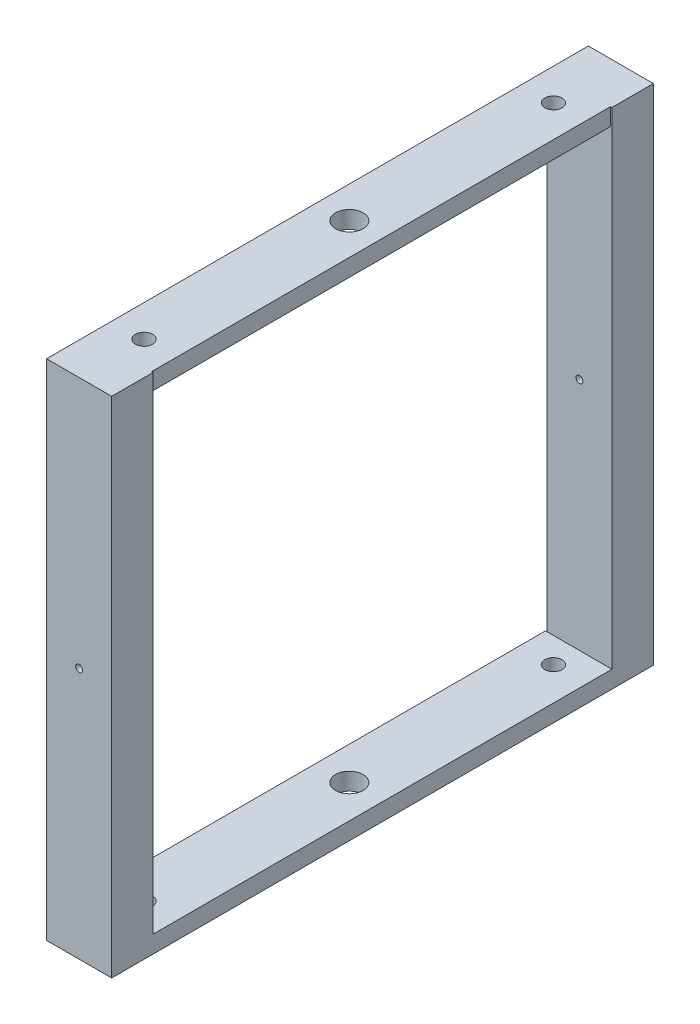
SolidWorks part; units mm, degrees
ref_plane "Front Plane" through (0, 0, 0) normal (0, 0, 1) x (1, 0, 0)
ref_plane "Top Plane" through (0, 0, 0) normal (0, 1, 0) x (1, 0, 0)
ref_plane "Right Plane" through (0, 0, 0) normal (1, 0, 0) x (0, 0, -1)
sketch "Sketch1" plane through (0, 0, 0) normal (0, 1, 0) x (1, 0, 0)
  line L1 (-66.5, -66.5) -> (66.5, -66.5)
  line L2 (-66.5, -66.5) -> (-66.5, 66.5)
  line L3 (-66.5, 66.5) -> (66.5, 66.5)
  line L4 (66.5, -66.5) -> (66.5, 66.5)
  line L5 (-66.5, -66.5) -> (66.5, 66.5) construction
  line L6 (-66.5, 66.5) -> (66.5, -66.5) construction
  point P0 (0, 0)
extrude "Boss-Extrude2" add sketch "Sketch1" along normal blind 136
sketch "Sketch2" plane through (0, 0, 66.5) normal (0, 0, 1) x (1, 0, 0)
  line L0 (66.5, 136) -> (66.5, 0) construction
  line L1 (-66.5, 136) -> (66.5, 136)
  line L2 (-66.5, 136) -> (-66.5, 127)
  line L3 (-66.5, 127) -> (66.5, 127)
  line L4 (66.5, 136) -> (66.5, 127)
  line L6 (-66.5, 0) -> (66.5, 0)
  line L7 (-66.5, 0) -> (-66.5, 9)
  line L8 (-66.5, 9) -> (66.5, 9)
  line L9 (66.5, 0) -> (66.5, 9)
  line L10 (-66.5, 127) -> (66.5, 127)
  line L11 (-66.5, 127) -> (-66.5, 9)
  line L12 (-66.5, 9) -> (66.5, 9)
  line L13 (66.5, 127) -> (66.5, 9)
  line M2 (66.5, 0) -> (66.5, 136)
  line M4 (-66.5, 136) -> (-66.5, 0)
extrude "Cut-Extrude1" cut sketch "Sketch2" against normal blind 136 contours L8 L3 M4 M2
sketch "Sketch4" plane through (0, 9, 0) normal (0, 1, 0) x (1, 0, 0)
  line L0 (0, 66.5) -> (0, -66.5) construction
  line L1 (-66.5, 66.5) -> (66.5, 66.5) construction
  line L2 (-66.5, -66.5) -> (66.5, -66.5) construction
  line L3 (0, -66.5) -> (33.25, -66.5) construction
  line L4 (33.25, -66.5) -> (33.25, 66.5) construction
  line L5 (0, 0) -> (66.5, 0) construction
  line L6 (66.5, 66.5) -> (66.5, -66.5) construction
  line L7 (66.5, 0) -> (66.5, 33.25) construction
  line L8 (66.5, 33.25) -> (0, 33.25) construction
  line L9 (0, 33.25) -> (0, -33.25) construction
  line L10 (0, -33.25) -> (66.5, -33.25) construction
  line L11 (43.75, 43.75) -> (22.75, 43.75)
  line L12 (43.75, -22.75) -> (22.75, -22.75)
  line L13 (43.75, -22.75) -> (43.75, -43.75)
  line L14 (43.75, -43.75) -> (22.75, -43.75)
  line L15 (22.75, -22.75) -> (22.75, -43.75)
  line L16 (43.75, -22.75) -> (22.75, -43.75) construction
  line L17 (43.75, -43.75) -> (22.75, -22.75) construction
  line L18 (46.25, -20.25) -> (20.25, -20.25)
  line L19 (46.25, -20.25) -> (46.25, -46.25)
  line L20 (46.25, -46.25) -> (20.25, -46.25)
  line L21 (20.25, -20.25) -> (20.25, -46.25)
  line L22 (46.25, -20.25) -> (20.25, -46.25) construction
  line L23 (46.25, -46.25) -> (20.25, -20.25) construction
  line L24 (22.75, 22.75) -> (22.75, 43.75)
  line L25 (43.75, 22.75) -> (22.75, 22.75)
  line L26 (43.75, 22.75) -> (43.75, 43.75)
  line L27 (46.25, 46.25) -> (20.25, 46.25)
  line L28 (20.25, 20.25) -> (20.25, 46.25)
  line L29 (46.25, 20.25) -> (20.25, 20.25)
  line L30 (46.25, 20.25) -> (46.25, 46.25)
  line L31 (46.25, 46.25) -> (20.25, 20.25) construction
  line L32 (46.25, 20.25) -> (20.25, 46.25) construction
  line L34 (43.75, -43.75) -> (46.25, -43.75)
  line L35 (43.75, -43.75) -> (43.75, -22.75)
  line L36 (43.75, -22.75) -> (46.25, -22.75)
  line L37 (46.25, -43.75) -> (46.25, -22.75)
  line L38 (43.75, 22.75) -> (46.25, 22.75)
  line L39 (43.75, 22.75) -> (43.75, 43.75)
  line L40 (43.75, 43.75) -> (46.25, 43.75)
  line L41 (46.25, 22.75) -> (46.25, 43.75)
  point P18 (33.25, -33.25)
  point P23 (33.25, -33.25)
  point P36 (33.25, 33.25)
extrude "Boss-Extrude3" add sketch "Sketch4" along normal blind 10.5 contours L12 L36 L19 L18 L21 L20 L34 L14 L15 | L11 L40 L30 L27 L28 L29 L38 L25 L24
sketch "Sketch5" plane through (22.75, 0, 0) normal (1, 0, 0) x (0, 0, -1)
  line L0 (-22.75, 19.5) -> (-22.75, 9) construction
  line L1 (-43.75, 19.5) -> (-22.75, 19.5)
  line L2 (-43.75, 19.5) -> (-43.75, 16.5)
  line L3 (-43.75, 16.5) -> (-22.75, 16.5)
  line L4 (-22.75, 19.5) -> (-22.75, 16.5)
  line L5 (43.75, 19.5) -> (43.75, 9) construction
  line L6 (22.75, 19.5) -> (43.75, 19.5)
  line L7 (22.75, 19.5) -> (22.75, 16.5)
  line L8 (22.75, 16.5) -> (43.75, 16.5)
  line L9 (43.75, 19.5) -> (43.75, 16.5)
extrude "Boss-Extrude4" add sketch "Sketch5" along normal up to surface (23.5 mm away) up to face at (46.25, 14.25, 45)
sketch "Sketch6" plane through (0, 19.5, 0) normal (0, 1, 0) x (1, 0, 0)
  line L0 (46.25, -46.25) -> (46.25, -20.25) construction
  line L1 (46.25, 20.25) -> (46.25, 46.25) construction
  line L2 (67.25, -41.85) -> (25.25, -41.85)
  line L3 (67.25, -41.85) -> (67.25, -24.65)
  line L4 (67.25, -24.65) -> (25.25, -24.65)
  line L5 (25.25, -41.85) -> (25.25, -24.65)
  line L6 (67.25, -41.85) -> (25.25, -24.65) construction
  line L7 (67.25, -24.65) -> (25.25, -41.85) construction
  line L9 (67.25, 24.65) -> (25.25, 24.65)
  line L10 (67.25, 24.65) -> (67.25, 41.85)
  line L11 (67.25, 41.85) -> (25.25, 41.85)
  line L12 (25.25, 24.65) -> (25.25, 41.85)
  line L13 (67.25, 24.65) -> (25.25, 41.85) construction
  line L14 (67.25, 41.85) -> (25.25, 24.65) construction
  point P4 (46.25, -33.25)
  point P13 (46.25, 33.25)
extrude "Cut-Extrude2" cut sketch "Sketch6" against normal up to surface (3 mm away) up to face at (34.5, 16.5, -33.25)
sketch "Sketch7" plane through (0, 127, 0) normal (0, -1, 0) x (1, 0, 0)
  line L0 (0, 66.5) -> (0, -66.5) construction
  line L1 (-66.5, 66.5) -> (66.5, 66.5) construction
  line L2 (-66.5, -66.5) -> (66.5, -66.5) construction
  line L3 (0, -66.5) -> (-33.25, -66.5) construction
  line L4 (-33.25, -66.5) -> (-33.25, 66.5) construction
  line L5 (-33.25, 66.5) -> (-66.5, 66.5) construction
  line L6 (-66.5, 66.5) -> (-66.5, 0) construction
  line L8 (-66.5, 0) -> (0, 0) construction
  line L9 (0, 0) -> (0, -33.25) construction
  line L10 (0, -33.25) -> (-66.5, -33.25) construction
  line L11 (-66.5, -66.5) -> (-66.5, 66.5) construction
  line L12 (-66.5, -33.25) -> (-66.5, 33.25) construction
  line L13 (-66.5, 33.25) -> (0, 33.25) construction
  line L14 (-22.75, -22.75) -> (-43.75, -22.75)
  line L15 (-22.75, 43.75) -> (-43.75, 43.75)
  line L16 (-22.75, 43.75) -> (-22.75, 22.75)
  line L17 (-22.75, 22.75) -> (-43.75, 22.75)
  line L18 (-43.75, 43.75) -> (-43.75, 22.75)
  line L19 (-22.75, 43.75) -> (-43.75, 22.75) construction
  line L20 (-22.75, 22.75) -> (-43.75, 43.75) construction
  line L21 (-20.25, 46.25) -> (-46.25, 46.25)
  line L22 (-20.25, 46.25) -> (-20.25, 20.25)
  line L23 (-20.25, 20.25) -> (-46.25, 20.25)
  line L24 (-46.25, 46.25) -> (-46.25, 20.25)
  line L25 (-20.25, 46.25) -> (-46.25, 20.25) construction
  line L26 (-20.25, 20.25) -> (-46.25, 46.25) construction
  line L27 (-43.75, -43.75) -> (-43.75, -22.75)
  line L28 (-22.75, -43.75) -> (-43.75, -43.75)
  line L29 (-22.75, -43.75) -> (-22.75, -22.75)
  line L30 (-20.25, -20.25) -> (-46.25, -20.25)
  line L31 (-46.25, -46.25) -> (-46.25, -20.25)
  line L32 (-20.25, -46.25) -> (-46.25, -46.25)
  line L33 (-20.25, -46.25) -> (-20.25, -20.25)
  line L34 (-20.25, -20.25) -> (-46.25, -46.25) construction
  line L35 (-20.25, -46.25) -> (-46.25, -20.25) construction
  line L36 (-43.75, -22.75) -> (-46.25, -22.75)
  line L37 (-43.75, 43.75) -> (-46.25, 43.75)
  line L38 (-43.75, 43.75) -> (-43.75, 22.75)
  line L39 (-43.75, 22.75) -> (-46.25, 22.75)
  line L40 (-46.25, 43.75) -> (-46.25, 22.75)
  line L41 (-46.25, -43.75) -> (-46.25, -22.75)
  line L42 (-43.75, -43.75) -> (-46.25, -43.75)
  line L43 (-43.75, -43.75) -> (-43.75, -22.75)
  point P17 (-33.25, 33.25)
  point P24 (-33.25, 33.25)
  point P37 (-33.25, -33.25)
extrude "Boss-Extrude5" add sketch "Sketch7" along normal blind 10.5 contours L17 L39 L24 L23 L22 L21 L37 L15 L16 | L28 L42 L31 L32 L33 L30 L36 L14 L29
sketch "Sketch8" plane through (-22.75, 0, 0) normal (-1, 0, 0) x (0, 0, 1)
  line L0 (22.75, 116.5) -> (22.75, 127) construction
  line L1 (43.75, 116.5) -> (22.75, 116.5)
  line L2 (43.75, 116.5) -> (43.75, 119.5)
  line L3 (43.75, 119.5) -> (22.75, 119.5)
  line L4 (22.75, 116.5) -> (22.75, 119.5)
  line L5 (-22.75, 116.5) -> (-22.75, 127) construction
  line L6 (-43.75, 116.5) -> (-22.75, 116.5)
  line L7 (-43.75, 116.5) -> (-43.75, 119.5)
  line L8 (-43.75, 119.5) -> (-22.75, 119.5)
  line L9 (-22.75, 116.5) -> (-22.75, 119.5)
extrude "Boss-Extrude6" add sketch "Sketch8" along normal up to surface (23.5 mm away) up to face at (-46.25, 121.75, 45)
sketch "Sketch9" plane through (0, 116.5, 0) normal (0, -1, 0) x (1, 0, 0)
  line L0 (-46.25, 46.25) -> (-46.25, 20.25) construction
  line L1 (-46.25, 20.25) -> (-46.25, -20.25) construction
  line L2 (-46.25, -20.25) -> (-46.25, -46.25) construction
  line L4 (-67.25, 41.85) -> (-25.25, 41.85)
  line L5 (-67.25, 41.85) -> (-67.25, 24.65)
  line L6 (-67.25, 24.65) -> (-25.25, 24.65)
  line L7 (-25.25, 41.85) -> (-25.25, 24.65)
  line L8 (-67.25, 41.85) -> (-25.25, 24.65) construction
  line L9 (-67.25, 24.65) -> (-25.25, 41.85) construction
  line L10 (-67.25, -24.65) -> (-25.25, -24.65)
  line L11 (-67.25, -24.65) -> (-67.25, -41.85)
  line L12 (-67.25, -41.85) -> (-25.25, -41.85)
  line L13 (-25.25, -24.65) -> (-25.25, -41.85)
  line L14 (-67.25, -24.65) -> (-25.25, -41.85) construction
  line L15 (-67.25, -41.85) -> (-25.25, -24.65) construction
  point P4 (-46.25, 33.25)
  point P13 (-46.25, -33.25)
extrude "Cut-Extrude3" cut sketch "Sketch9" against normal up to surface (3 mm away) up to face at (-34.5, 119.5, 33.25)
sketch "Sketch10" plane through (0, 0, 0) normal (0, -1, 0) x (1, 0, 0)
  line L0 (-66.5, -66.5) -> (66.5, -66.5) construction
  line L1 (66.5, -66.5) -> (0, -66.5) construction
  line L2 (0, -66.5) -> (0, 66.5) construction
  line L3 (-66.5, 66.5) -> (66.5, 66.5) construction
  line L5 (-9.6307, -66.5) -> (9.6307, -66.5)
  line L6 (-9.6307, -66.5) -> (-9.6307, 66.5)
  line L7 (-9.6307, 66.5) -> (9.6307, 66.5)
  line L8 (9.6307, -66.5) -> (9.6307, 66.5)
  line L9 (-9.6307, -66.5) -> (9.6307, 66.5) construction
  line L10 (-9.6307, 66.5) -> (9.6307, -66.5) construction
  point P4 (0, 0)
extrude "Boss-Extrude7" add sketch "Sketch10" along normal blind 5
sketch "Sketch11" plane through (0, 136, 0) normal (0, 1, 0) x (1, 0, 0)
  line L0 (-66.5, -66.5) -> (66.5, -66.5) construction
  line L1 (66.5, -66.5) -> (0, -66.5) construction
  line L2 (0, -66.5) -> (0, 66.5) construction
  line L3 (66.5, 66.5) -> (-66.5, 66.5) construction
  line L4 (0, 66.5) -> (0, 0) construction
  line L6 (-9.2186, -66.5) -> (9.2186, -66.5)
  line L7 (-9.2186, -66.5) -> (-9.2186, 66.5)
  line L8 (-9.2186, 66.5) -> (9.2186, 66.5)
  line L9 (9.2186, -66.5) -> (9.2186, 66.5)
  line L10 (-9.2186, -66.5) -> (9.2186, 66.5) construction
  line L11 (-9.2186, 66.5) -> (9.2186, -66.5) construction
extrude "Boss-Extrude8" add sketch "Sketch11" along normal blind 5
sketch "Sketch12" plane through (0, 0, -66.5) normal (0, 0, -1) x (-1, 0, 0)
  line L1 (-9.6307, -5) -> (9.2186, -5)
  line L2 (-9.6307, -5) -> (-9.6307, 141)
  line L3 (-9.6307, 141) -> (9.2186, 141)
  line L4 (9.2186, -5) -> (9.2186, 141)
extrude "Boss-Extrude9" add sketch "Sketch12" along normal blind 12
sketch "Sketch14" plane through (0, 0, 66.5) normal (0, 0, 1) x (1, 0, 0)
  line L1 (-9.2186, 141) -> (9.6307, 141)
  line L2 (-9.2186, 141) -> (-9.2186, -5)
  line L3 (-9.2186, -5) -> (9.6307, -5)
  line L4 (9.6307, 141) -> (9.6307, -5)
extrude "Boss-Extrude10" add sketch "Sketch14" along normal blind 12
sketch "Sketch17" plane through (0, 0, 78.5) normal (0, 0, 1) x (1, 0, 0)
  line L0 (-9.2186, 141) -> (9.6307, -5) construction
  line L1 (9.6307, -5) -> (0.2061, 68) construction
  circle A0 centre (0.2061, 68) radius 1
extrude "Cut-Extrude4" cut sketch "Sketch17" against normal through all
sketch "Sketch18" plane through (-66.5, 0, 0) normal (-1, 0, 0) x (0, 0, 1)
  line L0 (66.5, 9) -> (66.5, -5) construction
  line L1 (-66.5, 136) -> (66.5, 136)
  line L2 (-66.5, 136) -> (-66.5, 0)
  line L3 (-66.5, 0) -> (66.5, 0)
  line L4 (66.5, 136) -> (66.5, 0)
  line L5 (66.5, -5) -> (66.5, 0) construction
extrude "Cut-Extrude5" cut sketch "Sketch18" against normal blind 170
sketch "Sketch20" plane through (0, 0, 0) normal (0, 1, 0) x (1, 0, 0)
  circle A0 centre (0, 0) radius 2.5
extrude "Cut-Extrude6" cut sketch "Sketch20" against normal blind 10
sketch "Sketch21" plane through (0, -5, 0) normal (0, -1, 0) x (-1, 0, 0)
  circle A0 centre (2.8846, 0.7634) radius 0.25
sketch "Sketch22" plane through (0, 0, 0) normal (0, 1, 0) x (1, 0, 0)
  circle A0 centre (0, 0) radius 2.5
extrude "Cut-Extrude8" cut sketch "Sketch22" along normal blind 170
sketch "Sketch24" plane through (0, 0, 0) normal (0, 1, 0) x (1, 0, 0)
  circle A0 centre (0, 59.1598) radius 2.5
extrude "Cut-Extrude9" cut sketch "Sketch24" against normal blind 170
sketch "Sketch26" plane through (0, 9, 0) normal (0, 1, 0) x (1, 0, 0)
  circle A0 centre (0, 59.1598) radius 2.4747
extrude "Cut-Extrude10" cut sketch "Sketch26" along normal blind 177
sketch "Sketch27" plane through (0, 0, 0) normal (0, 1, 0) x (1, 0, 0)
  circle A0 centre (0, -59.4995) radius 2.5
extrude "Cut-Extrude11" cut sketch "Sketch27" against normal blind 177
sketch "Sketch29" plane through (0, -5, 0) normal (0, -1, 0) x (1, 0, 0)
  circle A0 centre (0, 59.4995) radius 2.5
extrude "Cut-Extrude12" cut sketch "Sketch29" against normal blind 177
sketch "Sketch31" plane through (0, 141, 0) normal (0, 1, 0) x (1, 0, 0)
  circle A0 centre (0, 0) radius 4
extrude "Cut-Extrude13" cut sketch "Sketch31" against normal blind 173
